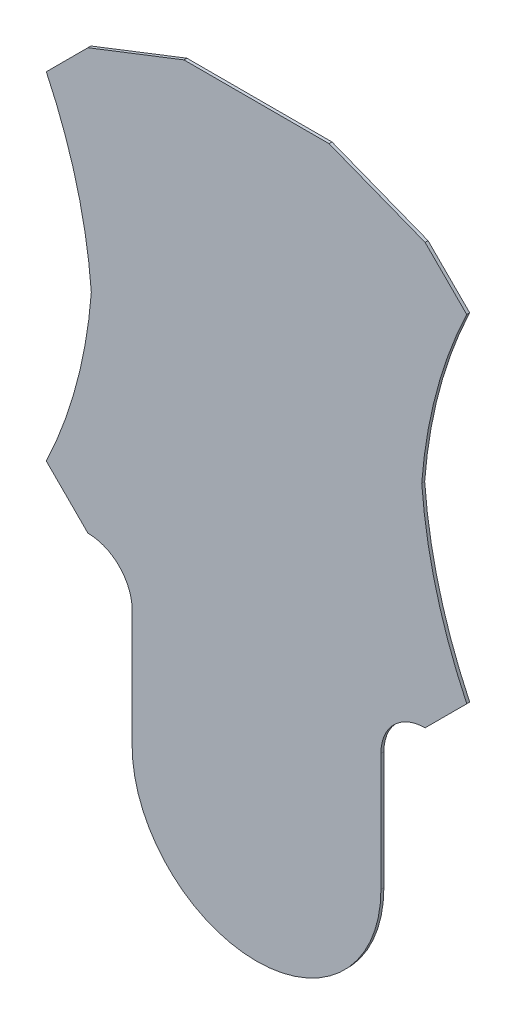
SolidWorks part; units mm, degrees
ref_plane "Front Plane" through (0, 0, 0) normal (0, 0, 1) x (1, 0, 0)
ref_plane "Top Plane" through (0, 0, 0) normal (0, 1, 0) x (1, 0, 0)
ref_plane "Right Plane" through (0, 0, 0) normal (1, 0, 0) x (0, 0, -1)
sketch "Sketch1" plane through (0, 0, 0) normal (0, 0, 1) x (1, 0, 0)
  line L0 (0, 250) -> (0, -49750) construction
  line L1 (-150, 0) -> (49850, 0) construction
  line L2 (0, 0) -> (35355.3391, 35355.3391) construction
  line L3 (0, 0) -> (0, 50000) construction
  line L4 (0, 0) -> (35355.3391, -35355.3391) construction
  line L5 (-128.6239, 128.6239) -> (0, 257.2479) construction
  line L6 (-128.6239, 128.6239) -> (-0.1663, 0.1663) construction
  line L7 (0, 0) -> (35355.3391, 35355.3391) construction
  line L8 (0, 257.2479) -> (128.4577, 128.7902) construction
  line L9 (-0.1663, 0.1663) -> (128.4577, 128.7902) construction
  line L10 (-142.7661, 114.4818) -> (-114.4818, 142.7661)
  line L11 (-114.4818, 142.7661) -> (-49.2676, 168.2043)
  line L12 (-49.2676, 168.2043) -> (49.2676, 168.2043)
  line L13 (142.7661, 114.4818) -> (114.4818, 142.7661)
  line L14 (114.4818, 142.7661) -> (49.2676, 168.2043)
  line L15 (-142.7661, -114.4818) -> (-114.4818, -142.7661)
  line L16 (-114.4818, -145.1786) -> (-114.4818, -50145.1786) construction
  line L17 (-108.0257, -142.7661) -> (49891.9743, -142.7661) construction
  line L18 (0, -172.7661) -> (50000, -172.7661) construction
  line L19 (-84.4818, -172.7661) -> (-84.4818, -252.7661)
  line L20 (142.7661, -114.4818) -> (114.4818, -142.7661)
  line L21 (84.4818, -172.7661) -> (84.4818, -252.7661)
  arc A0 (-142.7661, 114.4818) -> (-112.1926, 0) centre (-433.1053, -24.3794) cw
  arc A1 (142.7661, 114.4818) -> (112.1926, 0) centre (433.1053, -24.3794) ccw
  arc A2 (-142.7661, -114.4818) -> (-112.1926, 0) centre (-433.1053, 24.3794) ccw
  arc A3 (-114.4818, -142.7661) -> (-84.4818, -172.7661) centre (-114.4818, -172.7661) cw
  arc A4 (142.7661, -114.4818) -> (112.1926, 0) centre (433.1053, 24.3794) cw
  arc A5 (114.4818, -142.7661) -> (84.4818, -172.7661) centre (114.4818, -172.7661) ccw
  arc A6 (-84.4818, -252.7661) -> (84.4818, -252.7661) centre (0, -252.7661) ccw
  ellipse E0 centre (0, 0) end of major axis (0, 250) minor radius 150
  point P21 (0, 211.9402)
  point P35 (0, 168.2043)
  dimension "D1" = 30
extrude "Boss-Extrude1" add sketch "Sketch1" along normal blind 2 contours A1 A4 L20 A5 L21 A6 L19 A3 L15 A2 A0 L10 L11 L12 L14 L13
sketch "Sketch2" plane through (0, 0, 2) normal (0, 0, 1) x (1, 0, 0)
  line L1 (-142.7661, -114.4818) -> (-114.4818, -142.7661) construction
  line L3 (-84.4818, -172.7661) -> (-84.4818, -252.7661) construction
  circle A0 centre (-234.4818, -217.2479) radius 88.9
  arc A1 (-84.4818, -252.7661) -> (84.4818, -252.7661) centre (0, -252.7661) ccw construction
  point P4 (-128.6239, -128.6239)
  point P7 (0, -337.2479)
  dimension "D1" = 177.8
  dimension "D2" = 150
  dimension "D3" = 120
